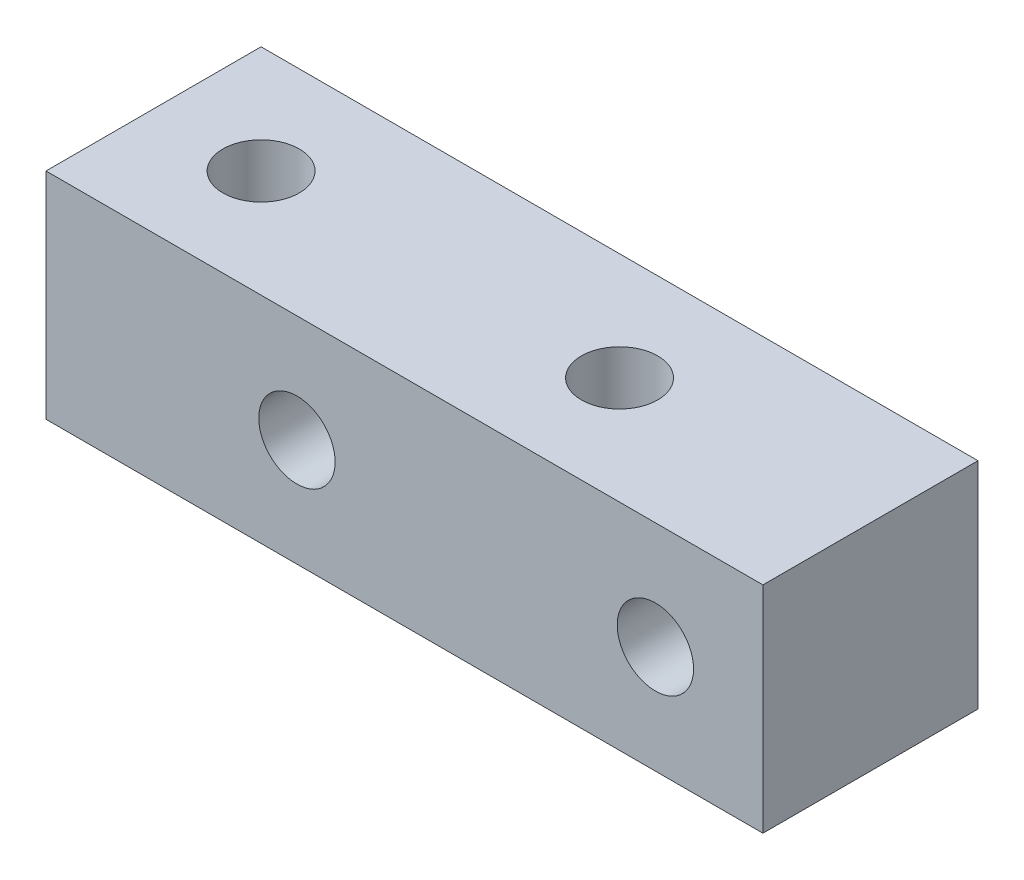
SolidWorks part; units mm, degrees
ref_plane "Front Plane" through (0, 0, 0) normal (0, 0, 1) x (1, 0, 0)
ref_plane "Top Plane" through (0, 0, 0) normal (0, 1, 0) x (1, 0, 0)
ref_plane "Right Plane" through (0, 0, 0) normal (1, 0, 0) x (0, 0, -1)
sketch "Sketch1" plane through (0, 0, 0) normal (0, 1, 0) x (1, 0, 0)
  line L1 (12.7, -3.81) -> (-12.7, -3.81)
  line L2 (12.7, -3.81) -> (12.7, 3.81)
  line L3 (12.7, 3.81) -> (-12.7, 3.81)
  line L4 (-12.7, -3.81) -> (-12.7, 3.81)
  line L5 (12.7, -3.81) -> (-12.7, 3.81) construction
  line L6 (12.7, 3.81) -> (-12.7, -3.81) construction
  point P0 (0, 0)
  dimension "D1" = 25.4
  dimension "D2" = 7.62
extrude "Boss-Extrude1" add sketch "Sketch1" along normal mid plane 7.62
hole_wizard "Tap Drill for #6-32 Tap1" positions "Sketch2" profile "Sketch3" hole size "#6-32" standard "ANSI Inch" end condition through all
sketch "Sketch2" plane through (0, 3.81, 0) normal (0, 1, 0) x (1, 0, 0)
  line L0 (-8.89, 0) -> (3.81, 0)
  line L2 (-12.7, -3.81) -> (12.7, -3.81) construction
  line L3 (-12.7, 3.81) -> (-12.7, -3.81) construction
  point P0 (-8.89, 0)
  point P2 (3.81, 0)
  dimension "D1" = 3.81
  dimension "D2" = 12.7
  dimension "D3" = 3.81
sketch "Sketch3" plane through (-8.89, 3.81, 0) normal (1, 0, 0) x (0, 0, 1)
  line L0 (0, 0) -> (0, 7.62)
  line L1 (0, 7.62) -> (1.3525, 7.62)
  line L2 (1.3525, 7.62) -> (1.3525, 0)
  line L5 (1.3525, 0) -> (0, 0)
  line L11 (0, -6.35) -> (0, 107.95) construction
  dimension "Thru Hole Dia." = 2.7051
  dimension "Thru Hole Depth" = 7.62
hole_wizard "Tap Drill for #6-32 Tap2" positions "Sketch4" profile "Sketch5" hole size "#6-32" standard "ANSI Inch" end condition through all
sketch "Sketch4" plane through (0, 0, 3.81) normal (0, 0, 1) x (1, 0, 0)
  line L0 (-3.81, 0) -> (8.89, 0)
  line L2 (12.7, 3.81) -> (12.7, -3.81) construction
  point P0 (-3.81, 0)
  point P2 (8.89, 0)
  dimension "D1" = 12.7
  dimension "D2" = 3.81
sketch "Sketch5" plane through (-3.81, 0, 3.81) normal (1, 0, 0) x (0, -1, 0)
  line L0 (0, 0) -> (0, 7.62)
  line L1 (0, 7.62) -> (1.3525, 7.62)
  line L2 (1.3525, 7.62) -> (1.3525, 0)
  line L5 (1.3525, 0) -> (0, 0)
  line L11 (0, -6.35) -> (0, 107.95) construction
  dimension "Thru Hole Dia." = 2.7051
  dimension "Thru Hole Depth" = 7.62
